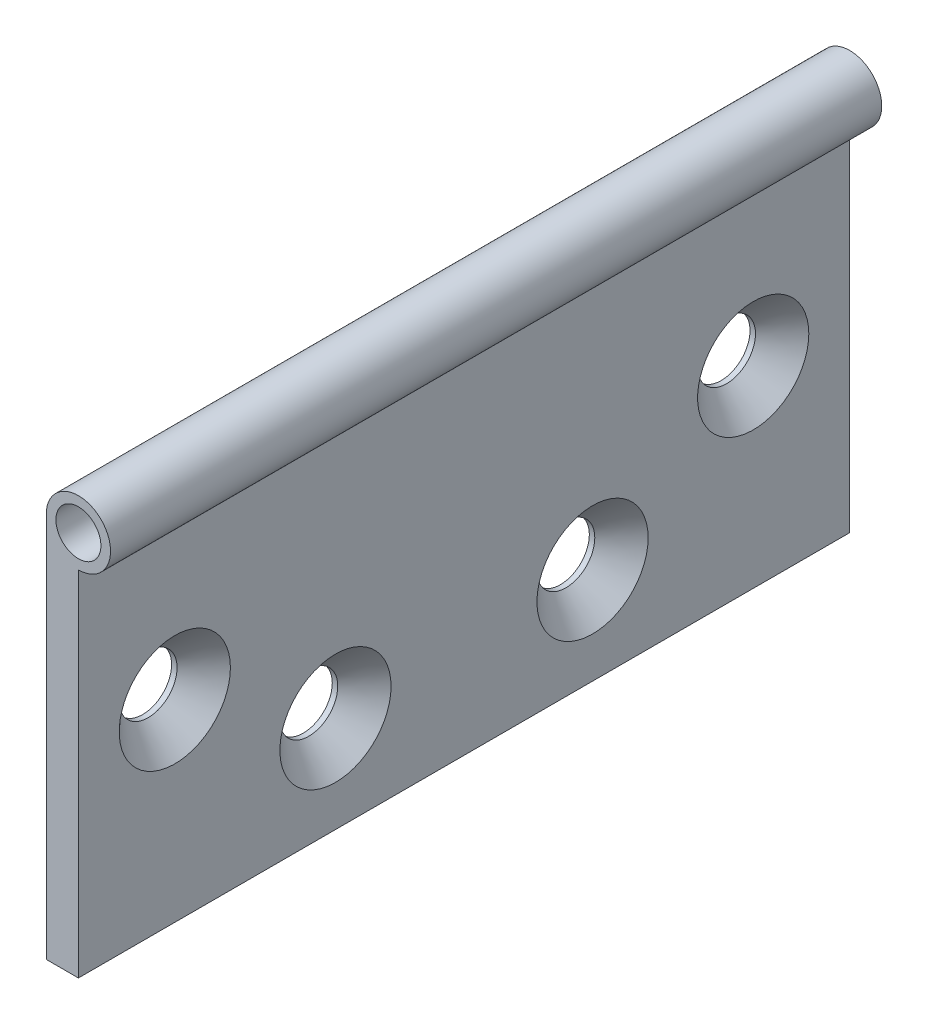
SolidWorks part; units mm, degrees
ref_plane "Front Plane" through (0, 0, 0) normal (0, 0, 1) x (1, 0, 0)
ref_plane "Top Plane" through (0, 0, 0) normal (0, 1, 0) x (1, 0, 0)
ref_plane "Right Plane" through (0, 0, 0) normal (1, 0, 0) x (0, 0, -1)
sketch "Эскиз1" plane through (0, 0, 0) normal (0, 0, 1) x (1, 0, 0)
  line L0 (0, 0) -> (0, 60)
  dimension "D1" = 60
extrude "Вытянуть-Тонкостенный1" add sketch "Эскиз1" along normal mid plane 120 thin
sketch "Эскиз2" plane through (0, 0, 60) normal (0, 0, 1) x (1, 0, 0)
  circle A0 centre (5, 60) radius 5
sweep "По траектории1" add profiles "Эскиз2" path edge at (5, 60, 0)
sketch "Эскиз4" plane through (0, 0, 60) normal (0, 0, 1) x (1, 0, 0)
  circle A0 centre (5, 60) radius 3.5
  arc A1 (5, 55) -> (0, 60) centre (5, 60) ccw construction
extrude "Вырез-Вытянуть1" cut sketch "Эскиз4" against normal through all
hole_wizard "Зенковка для  винта с плоской головкой M81" positions "Эскиз6" profile "Эскиз5" countersink size "M8" standard "Ansi Metric" end condition through all
sketch "Эскиз6" plane through (5, 0, 0) normal (1, 0, 0) x (0, 0, -1)
  point P0 (-45, 30)
  point P2 (-20, 15)
  dimension "D1" = 30
  dimension "D2" = 15
  dimension "D3" = 15
  dimension "D4" = 40
sketch "Эскиз5" plane through (5, 30, 45) normal (0, 1, 0) x (0, 0, -1)
  line L0 (0, 0) -> (0, 5)
  line L1 (0, 5) -> (4.5, 5)
  line L2 (4.5, 5) -> (4.5, 4.15)
  line L3 (4.5, 4.15) -> (8.65, 0)
  line L5 (8.65, 0) -> (0, 0)
  line L6 (-4.5, 4.15) -> (-8.65, 0) construction
  line L11 (0, -6.35) -> (0, 107.95) construction
  dimension "Диаметр сквозного отверстия" = 9
  dimension "Глубина сквозного отверстия" = 5
  dimension "Диаметр передней зенковки" = 17.3
  dimension "Угол передней зенковки" = 90
mirror "Зеркальное отражение1" about plane through (0, 0, 0) normal (0, 0, 1) of "Зенковка для  винта с плоской головкой M81"
sketch "компоновка для вырезов" plane through (5, 0, 0) normal (1, 0, 0) x (0, 0, -1)
  line L5 (-60, 65) -> (-60, 55) construction
  line L6 (60, 54) -> (-60, 54)
  line L7 (60, 54) -> (-60, 54)
  line L8 (60, 55) -> (60, 65) construction
  line L9 (-60, 65) -> (-60, 54)
  line L10 (60, 54) -> (60, 65)
  line L11 (-36, 65) -> (-36, 54)
  line L12 (-12, 65) -> (-12, 54)
  line L13 (60, 65) -> (-60, 65) construction
  line L14 (0, 96.9295) -> (0, 0) construction
  line L15 (12, 65) -> (12, 54)
  line L16 (36, 65) -> (36, 54)
  dimension "D2" = 24
  dimension "D3" = 24
  dimension "D1" = 1
equation "\"D1@Эскиз6\"= \"D1@Эскиз1\" / 2"
equation "\"D4@Эскиз6\"= \"D1@Вытянуть-Тонкостенный1\" / 3"
equation "\"D2@компоновка для вырезов\"= \"D1@Вытянуть-Тонкостенный1\" / 5"
equation "\"D3@компоновка для вырезов\"= \"D1@Вытянуть-Тонкостенный1\" / 5"
